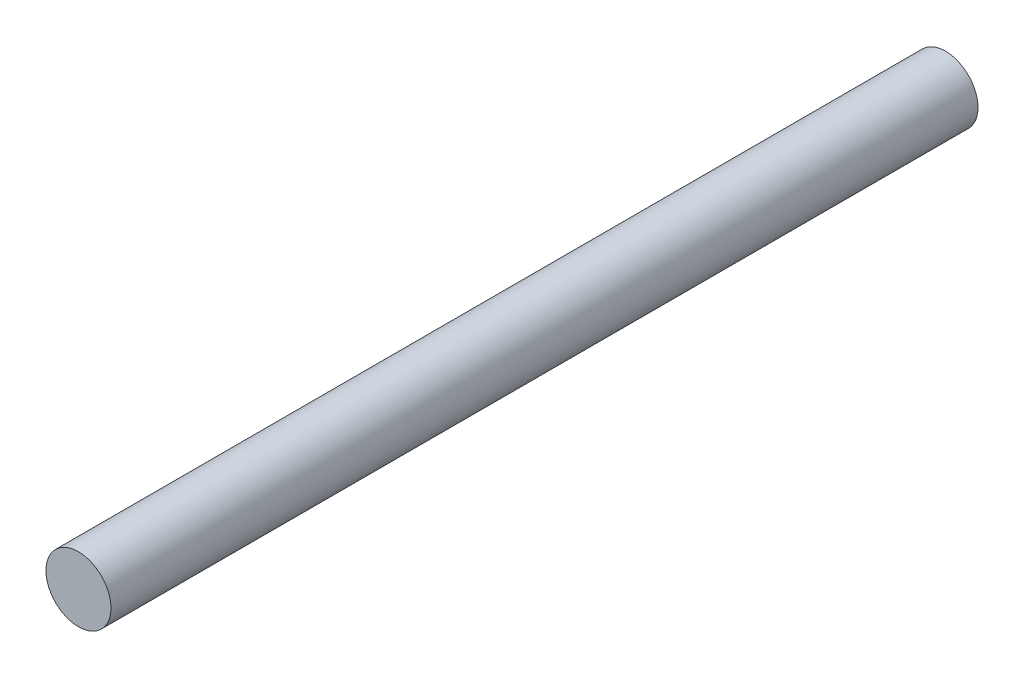
SolidWorks part; units mm, degrees
ref_plane "Front Plane" through (0, 0, 0) normal (0, 0, 1) x (1, 0, 0)
ref_plane "Top Plane" through (0, 0, 0) normal (0, 1, 0) x (1, 0, 0)
ref_plane "Right Plane" through (0, 0, 0) normal (1, 0, 0) x (0, 0, -1)
sketch "Sketch1" plane through (0, 0, 0) normal (0, 0, 1) x (1, 0, 0)
  circle A0 centre (0, 0) radius 7.5
  dimension "D1" = 15
extrude "Boss-Extrude1" add sketch "Sketch1" along normal blind 200
